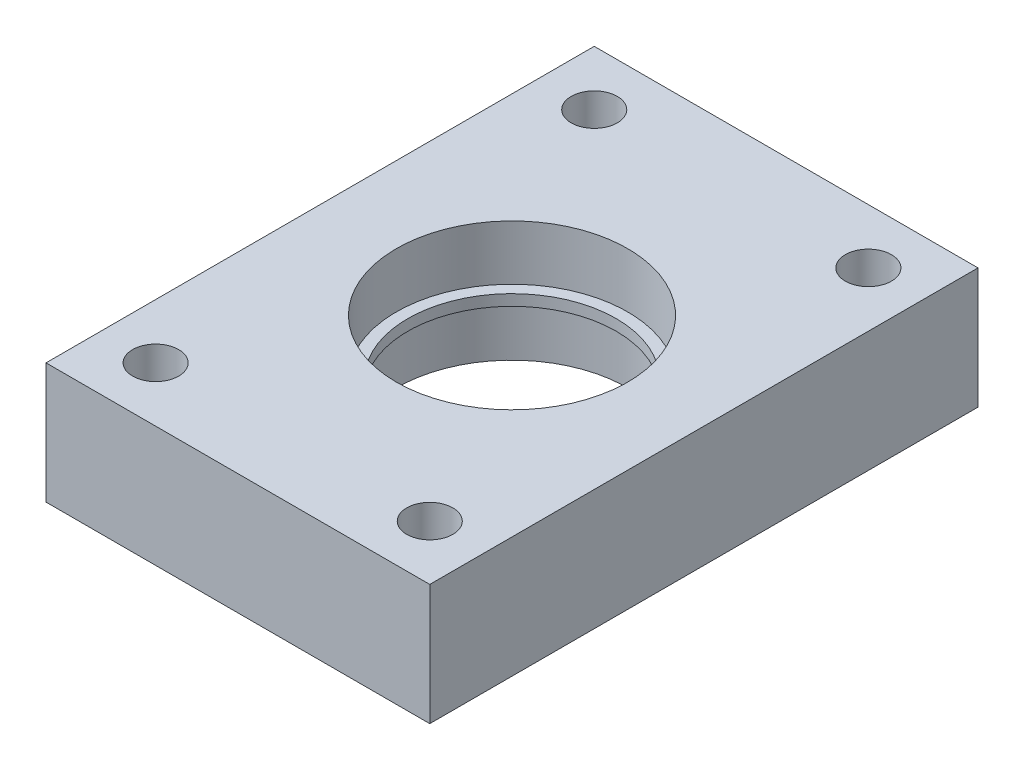
SolidWorks part; units mm, degrees
ref_plane "前视基准面" through (0, 0, 0) normal (0, 0, 1) x (1, 0, 0)
ref_plane "上视基准面" through (0, 0, 0) normal (0, 1, 0) x (1, 0, 0)
ref_plane "右视基准面" through (0, 0, 0) normal (1, 0, 0) x (0, 0, -1)
sketch "草图1" plane through (0, 0, 0) normal (0, 1, 0) x (1, 0, 0)
  line L0 (0, 27.4369) -> (0, -46.0914) construction
  line L1 (-17.5, 0) -> (-17.5, -25)
  line L2 (-17.5, -25) -> (17.5, -25)
  line L3 (17.5, 0) -> (17.5, -25)
  line L4 (17.5, 0) -> (17.5, 25)
  line L5 (17.5, 25) -> (-17.5, 25)
  line L6 (-17.5, 25) -> (-17.5, 0)
  circle A0 centre (0, 0) radius 9.5
  point P10 (0, -25)
  dimension "D1" = 19
  dimension "D3" = 25
extrude "凸台-拉伸1" add sketch "草图1" along normal blind 11
sketch "草图2" plane through (0, 11, 0) normal (0, 1, 0) x (1, 0, 0)
  circle A0 centre (0, 0) radius 10.55
  dimension "D1" = 21.1
extrude "切除-拉伸1" cut sketch "草图2" against normal blind 5
ref_plane "基准面1" through (0, 5.5, 0) normal (0, 1, 0) x (1, 0, 0)
mirror "镜向1" about plane through (0, 5.5, 0) normal (0, 1, 0) of "切除-拉伸1"
sketch "草图3" plane through (0, 0, 0) normal (0, -1, 0) x (1, 0, 0)
  line L0 (17.5, 25) -> (17.5, -25) construction
  line L1 (-17.5, 25) -> (17.5, 25)
  line L2 (-17.5, 25) -> (-17.5, 21)
  line L3 (-17.5, 21) -> (17.5, 21)
  line L4 (17.5, 25) -> (17.5, 21)
  dimension "D1" = 4
extrude "凸台-拉伸2" add sketch "草图3" along normal blind 31
sketch "草图5" plane through (0, -31, 0) normal (0, -1, 0) x (1, 0, 0)
  line L0 (-17.5, 25) -> (-17.5, 0)
  line L1 (17.5, 25) -> (17.5, 0)
  line L2 (-17.5, 25) -> (17.5, 25)
  line L3 (-28.7822, 0) -> (44.7616, 0) construction
  line L4 (0, 22.9458) -> (0, -31.2005) construction
  circle A0 centre (0, 0) radius 10.5
  arc A1 (-17.5, 0) -> (17.5, 0) centre (0, 0) ccw
  circle A2 centre (0, 14) radius 2.1
  circle A3 centre (0, 0) radius 14 construction
  circle A4 centre (14, 0) radius 2.1
  circle A5 centre (0, -14) radius 2.1
  circle A6 centre (-14, 0) radius 2.1
  point P25 (0, 0)
  dimension "D1" = 4.2
  dimension "D2" = 28
  dimension "D3" = 4
extrude "凸台-拉伸3" add sketch "草图5" along normal blind 3.5
sketch "草图7" plane through (-17.5, 0, 0) normal (-1, 0, 0) x (0, 0, 1)
  line L1 (27.2517, 0) -> (-34.2817, 0)
  line L2 (27.2517, 0) -> (27.2517, -39.3619)
  line L3 (27.2517, -39.3619) -> (-34.2817, -39.3619)
  line L4 (-34.2817, 0) -> (-34.2817, -39.3619)
extrude "切除-拉伸4" cut sketch "草图7" against normal through all
sketch "草图8" plane through (0, 0, 0) normal (0, -1, 0) x (1, 0, 0)
  line L0 (0, 0) -> (0, 25) construction
  line L1 (-17.5, 25) -> (17.5, 25) construction
  line L2 (-12.5, 25) -> (-12.5, -25) construction
  line L3 (17.5, -25) -> (-17.5, -25) construction
  line L4 (-17.5, -25) -> (-17.5, 25) construction
  line L5 (0, 0) -> (16.1011, 0) construction
  line L7 (-12.5, 20) -> (12.5, 20) construction
  line L8 (-12.5, 20) -> (-12.5, -20) construction
  line L9 (-12.5, -20) -> (12.5, -20) construction
  line L10 (12.5, 20) -> (12.5, -20) construction
  circle A0 centre (-12.5, 20) radius 2.1
  circle A1 centre (12.5, 20) radius 2.1
  circle A2 centre (12.5, -20) radius 2.1
  circle A3 centre (-12.5, -20) radius 2.1
  dimension "D3" = 4.2
  dimension "D1" = 5
  dimension "D2" = 5
extrude "切除-拉伸5" cut sketch "草图8" against normal blind 20
sketch "草图9" plane through (0, 0, 0) normal (0, -1, 0) x (1, 0, 0)
  line L0 (0, 0) -> (37.7333, 0) construction
  line L1 (0, 0) -> (0, 38.8789) construction
  line L2 (17.5, -25) -> (-17.5, -25) construction
  line L4 (17.5, -25) -> (17.5, 25)
  line L5 (17.5, 25) -> (-17.5, 25)
  line L6 (-17.5, 25) -> (-17.5, -25)
  line L7 (-17.5, -25) -> (17.5, -25)
  line L8 (17.5, -25) -> (17.5, 25) construction
  line L9 (17.5, 25) -> (-17.5, 25) construction
  line L10 (-17.5, 25) -> (-17.5, -25) construction
  line L11 (-17.5, -25) -> (17.5, -25) construction
  circle A0 centre (-12.5, 20) radius 2.1 construction
  circle A1 centre (-12.5, 20) radius 2.1 construction
  circle A2 centre (12.5, 20) radius 2.1 construction
  circle A3 centre (12.5, 20) radius 2.1 construction
  circle A4 centre (-12.5, -20) radius 2.1 construction
  circle A5 centre (-12.5, -20) radius 2.1 construction
  circle A6 centre (12.5, -20) radius 2.1 construction
  circle A7 centre (12.5, -20) radius 2.1 construction
  circle A8 centre (-12.5, 20) radius 3.8
  circle A9 centre (12.5, 20) radius 3.8
  circle A10 centre (12.5, -20) radius 2.1 construction
  circle A11 centre (-12.5, -20) radius 2.1 construction
  circle A12 centre (12.5, -20) radius 3.8
  circle A13 centre (-12.5, -20) radius 3.8
  dimension "D2" = 7.6
  dimension "D1" = 0
extrude "切除-拉伸6" cut sketch "草图9" against normal blind 2.2
